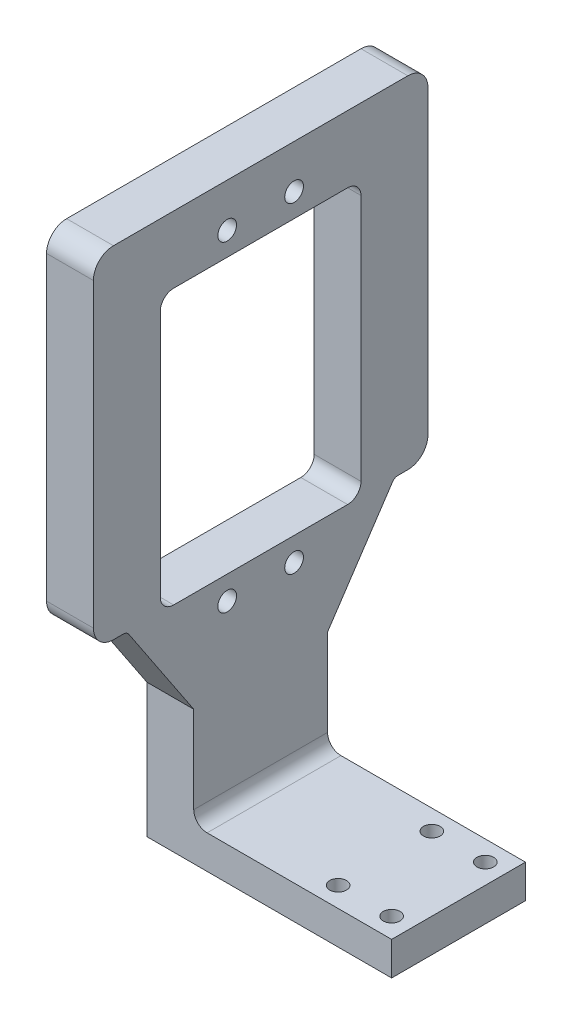
SolidWorks part; units mm, degrees
ref_plane "Front Plane" through (0, 0, 0) normal (0, 0, 1) x (1, 0, 0)
ref_plane "Top Plane" through (0, 0, 0) normal (0, 1, 0) x (1, 0, 0)
ref_plane "Right Plane" through (0, 0, 0) normal (1, 0, 0) x (0, 0, -1)
sketch "Sketch1" plane through (0, 0, 0) normal (0, 1, 0) x (1, 0, 0)
  line L0 (0, 10) -> (36.58, 10) construction
  line L1 (0, 0) -> (36.58, 0)
  line L2 (0, 0) -> (0, 20)
  line L3 (0, 20) -> (36.58, 20)
  line L4 (36.58, 0) -> (36.58, 20)
  circle A0 centre (25.58, 3) radius 1.25
  circle A1 centre (33.58, 3) radius 1.25
  circle A2 centre (33.58, 17) radius 1.25
  circle A3 centre (25.58, 17) radius 1.25
  dimension "D3" = 2.5
  dimension "D1" = 36.58
  dimension "D2" = 20
  dimension "D4" = 3
  dimension "D5" = 3
  dimension "D6" = 8
extrude "Boss-Extrude1" add sketch "Sketch1" along normal blind 5
sketch "Sketch3" plane through (0, 0, 0) normal (-1, 0, 0) x (0, 0, 1)
  line L0 (0, 35) -> (5, 35)
  line L1 (-20, 5) -> (0, 5)
  line L2 (-20, 5) -> (-20, 35)
  line L3 (-20, 35) -> (0, 35)
  line L4 (0, 5) -> (0, 35)
  line L5 (5, 35) -> (15, 35)
  line L6 (5, 35) -> (5, 76)
  line L7 (5, 76) -> (15, 76)
  line L8 (15, 35) -> (15, 76)
  line L9 (-25, 35) -> (-35, 35)
  line L10 (-25, 35) -> (-25, 76)
  line L11 (-25, 76) -> (-35, 76)
  line L12 (-35, 35) -> (-35, 76)
  line L13 (-35, 86) -> (15, 86)
  line L14 (-35, 86) -> (-35, 76)
  line L15 (-35, 76) -> (15, 76)
  line L16 (15, 86) -> (15, 76)
  line L17 (-20, 35) -> (-25, 35)
  line L18 (-20, 20) -> (-30, 35)
  line L19 (0, 20) -> (10, 35)
  line M21 (0, 5) -> (-20, 5)
  dimension "D1" = 30
  dimension "D2" = 41
  dimension "D3" = 10
  dimension "D4" = 30
extrude "Boss-Extrude2" add sketch "Sketch3" against normal blind 7 contours L4 L3 L2 M21 | L18 L2 L17 L9 | L12 L9 L10 L11 | L16 L13 L14 L11 L15 L7 | L5 L8 L7 L6 | L4 L19 L5 L0
fillet "Fillet1" radius 3 4 edges at (3.5, 86, -35) (3.5, 86, 15) (3.5, 35, 15) (3.5, 35, -35)
fillet "Fillet2" radius 1 2 edges at (3.5, 35, 10) (3.5, 35, -30)
ref_plane "Plane1" through (0, 55.5, 0) normal (0, 1, 0) x (1, 0, 0)
ref_plane "Plane2" through (0, 0, -10) normal (0, 0, -1) x (-1, 0, 0)
sketch "Sketch6" plane through (0, 0, 0) normal (-1, 0, 0) x (0, 0, 1)
  line L0 (-10, 3.85) -> (-10, -3.85) construction
  line L1 (-25, 35) -> (5, 35) construction
  line L2 (3.85, 55.5) -> (-3.85, 55.5) construction
  circle A0 centre (-15, 31.5) radius 1.4
  circle A1 centre (-5, 31.5) radius 1.4
  circle A2 centre (-15, 79.5) radius 1.4
  circle A3 centre (-5, 79.5) radius 1.4
  dimension "D1" = 2.8
  dimension "D2" = 5
  dimension "D3" = 3.5
extrude "Cut-Extrude1" cut sketch "Sketch6" against normal up to next
fillet "Fillet3" radius 2 5 edges at (3.5, 76, 5) (3.5, 76, -25) (3.5, 35, -25) (3.5, 35, 5) (7, 5, -10)
